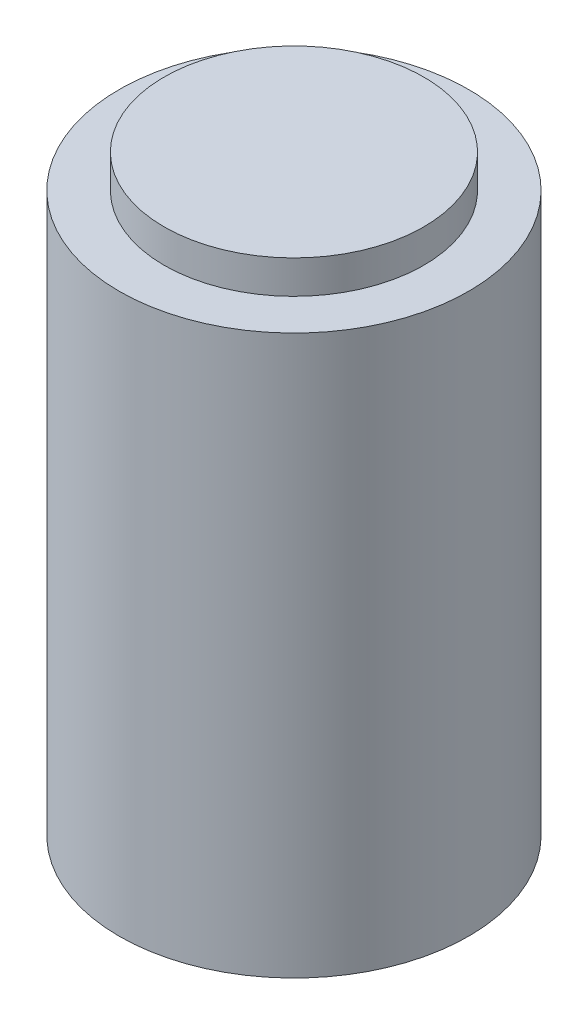
SolidWorks part; units mm, degrees
ref_plane "Front Plane" through (0, 0, 0) normal (0, 0, 1) x (1, 0, 0)
ref_plane "Top Plane" through (0, 0, 0) normal (0, 1, 0) x (1, 0, 0)
ref_plane "Right Plane" through (0, 0, 0) normal (1, 0, 0) x (0, 0, -1)
sketch "Sketch1" plane through (0, 0, 0) normal (0, 1, 0) x (1, 0, 0)
  circle A0 centre (0, 0) radius 26.25
  dimension "D1" = 52.5
extrude "Boss-Extrude1" add sketch "Sketch1" along normal blind 83.9
sketch "Sketch2" plane through (0, 0, 0) normal (0, -1, 0) x (1, 0, 0)
  circle A0 centre (0, 0) radius 14.01
  dimension "D1" = 28.02
extrude "Cut-Extrude1" cut sketch "Sketch2" against normal blind 75.9
sketch "Sketch4" plane through (0, 83.9, 0) normal (0, 1, 0) x (1, 0, 0)
  circle A0 centre (0, 0) radius 19.5
  dimension "D1" = 39
extrude "Boss-Extrude2" add sketch "Sketch4" along normal blind 5
